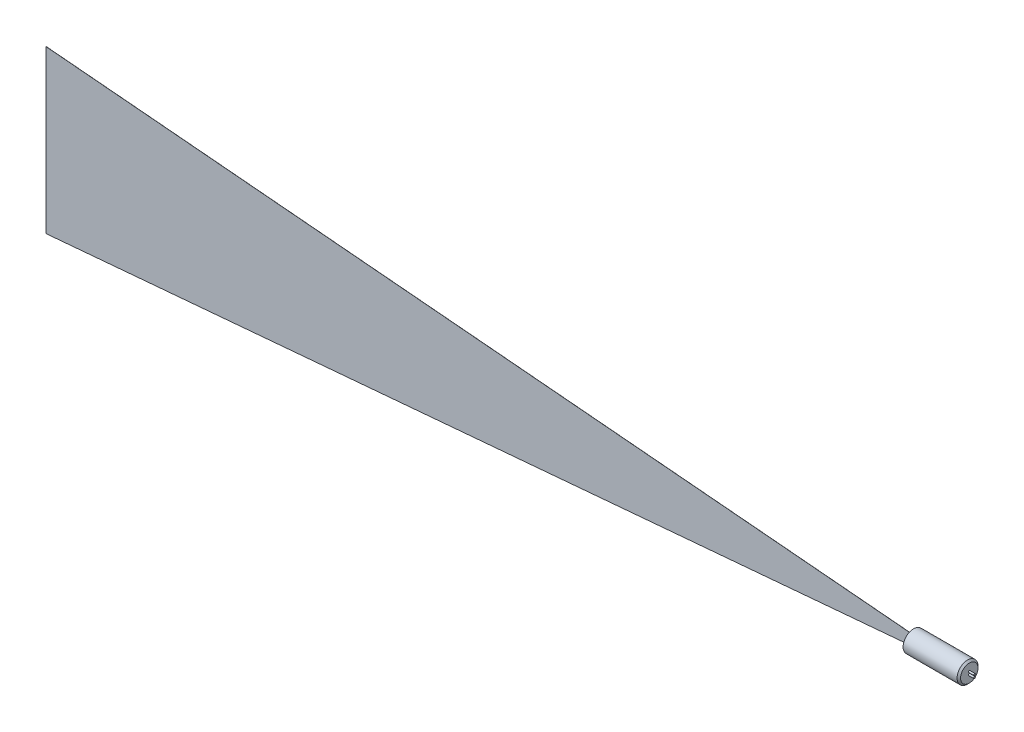
SolidWorks part; units mm, degrees
ref_plane "Plan de face" through (0, 0, 0) normal (0, 0, 1) x (1, 0, 0)
ref_plane "Plan de dessus" through (0, 0, 0) normal (0, 1, 0) x (1, 0, 0)
ref_plane "Plan de droite" through (0, 0, 0) normal (1, 0, 0) x (0, 0, -1)
sketch "Esquisse1" plane through (0, 0, 0) normal (1, 0, 0) x (0, 0, -1)
  circle A0 centre (0, 0) radius 6
  dimension "D1" = 12
extrude "Extrusion1" add sketch "Esquisse1" along normal blind 32
sketch "Esquisse2" plane through (0, 0, 0) normal (-1, 0, 0) x (0, 0, 1)
  circle A0 centre (0, 0) radius 3.4
  dimension "D1" = 6.8
extrude "Enlèv. mat.-Extru.1" cut sketch "Esquisse2" against normal blind 2
chamfer "Chanfrein1" distance 1 angle 45 1 edges at (32, 0, -6)
sketch "Esquisse3" plane through (32, 0, 0) normal (1, 0, 0) x (0, 0, -1)
  line L0 (0, 0) -> (0, 0.75) construction
  line L1 (-0.8557, 0) -> (0, 0) construction
  circle A0 centre (0, 0.75) radius 0.5
  circle A1 centre (0, -0.75) radius 0.5
  dimension "D2" = 1
  dimension "D1" = 0.75
extrude "Extrusion2" add sketch "Esquisse3" along normal blind 3
sketch "Esquisse4" plane through (0, 0, 0) normal (0, 0, 1) x (1, 0, 0)
  line L0 (-498, 0) -> (2, 0) construction
  line L1 (2, 2.75) -> (2, -2.75)
  line L3 (-498, 46.4943) -> (-498, -46.4943)
  line L4 (-498, 46.4943) -> (2, 2.75)
  line L5 (2, -2.75) -> (-498, -46.4943)
  line L6 (2, 3.4) -> (2, -3.4) construction
  dimension "D1" = 500
  dimension "D2" = 10
  dimension "D3" = 5.5
extrude "Extrusion3" add sketch "Esquisse4" along normal mid plane 0.1
